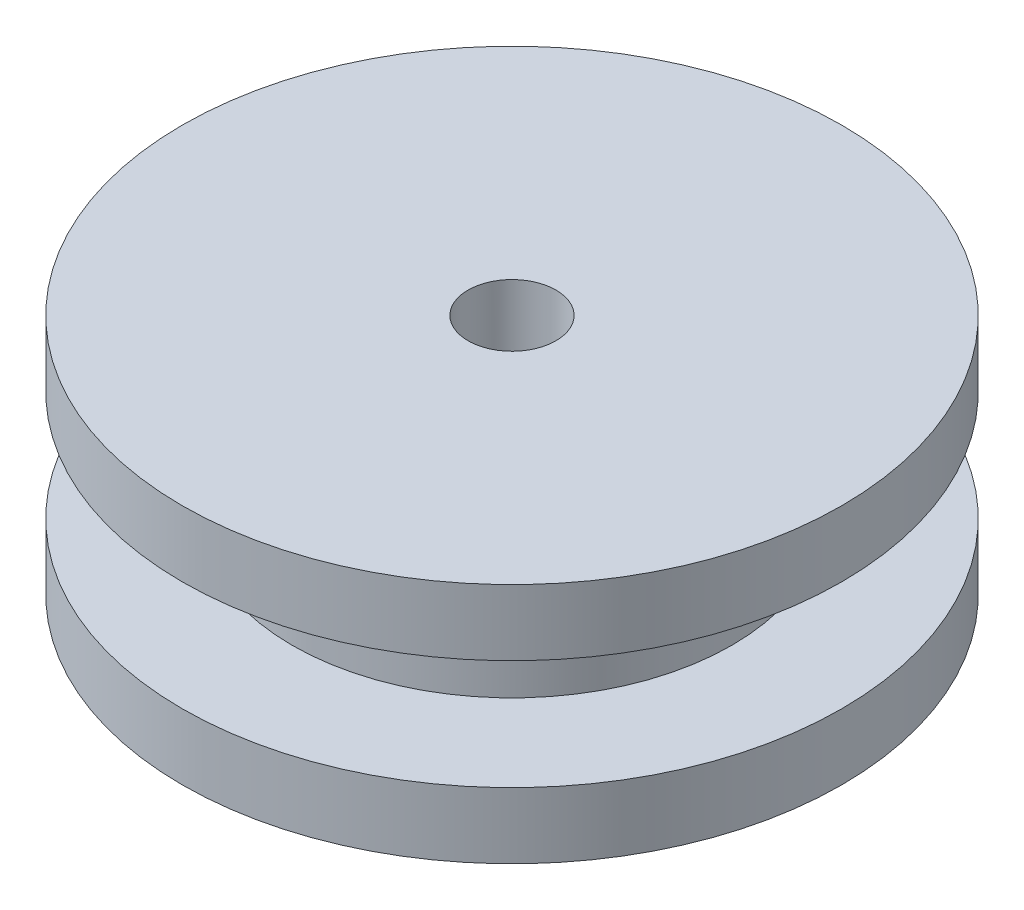
SolidWorks part; units mm, degrees
ref_plane "正面" through (0, 0, 0) normal (0, 0, 1) x (1, 0, 0)
ref_plane "平面" through (0, 0, 0) normal (0, 1, 0) x (1, 0, 0)
ref_plane "右側面" through (0, 0, 0) normal (1, 0, 0) x (0, 0, -1)
sketch "ｽｹｯﾁ1" plane through (0, 0, 0) normal (0, 1, 0) x (1, 0, 0)
  circle A0 centre (0, 0) radius 15
  dimension "D1" = 30
extrude "ﾎﾞｽ - 押し出し1" add sketch "ｽｹｯﾁ1" along normal blind 3
sketch "ｽｹｯﾁ2" plane through (0, 3, 0) normal (0, 1, 0) x (1, 0, 0)
  circle A0 centre (0, 0) radius 10
  circle A2 centre (0, 0) radius 15 construction
  dimension "D1" = 5
extrude "ﾎﾞｽ - 押し出し2" add sketch "ｽｹｯﾁ2" along normal blind 5
sketch "ｽｹｯﾁ3" plane through (0, 8, 0) normal (0, 1, 0) x (1, 0, 0)
  circle A1 centre (0, 0) radius 15
  circle A2 centre (0, 0) radius 15
  dimension "D1" = 0
extrude "ﾎﾞｽ - 押し出し3" add sketch "ｽｹｯﾁ3" along normal blind 3 separate body
sketch "ｽｹｯﾁ5" plane through (0, 0, 0) normal (0, -1, 0) x (1, 0, 0)
  circle A0 centre (0, 0) radius 2
  dimension "D1" = 4
extrude "ｶｯﾄ - 押し出し1" cut sketch "ｽｹｯﾁ5" against normal through all
